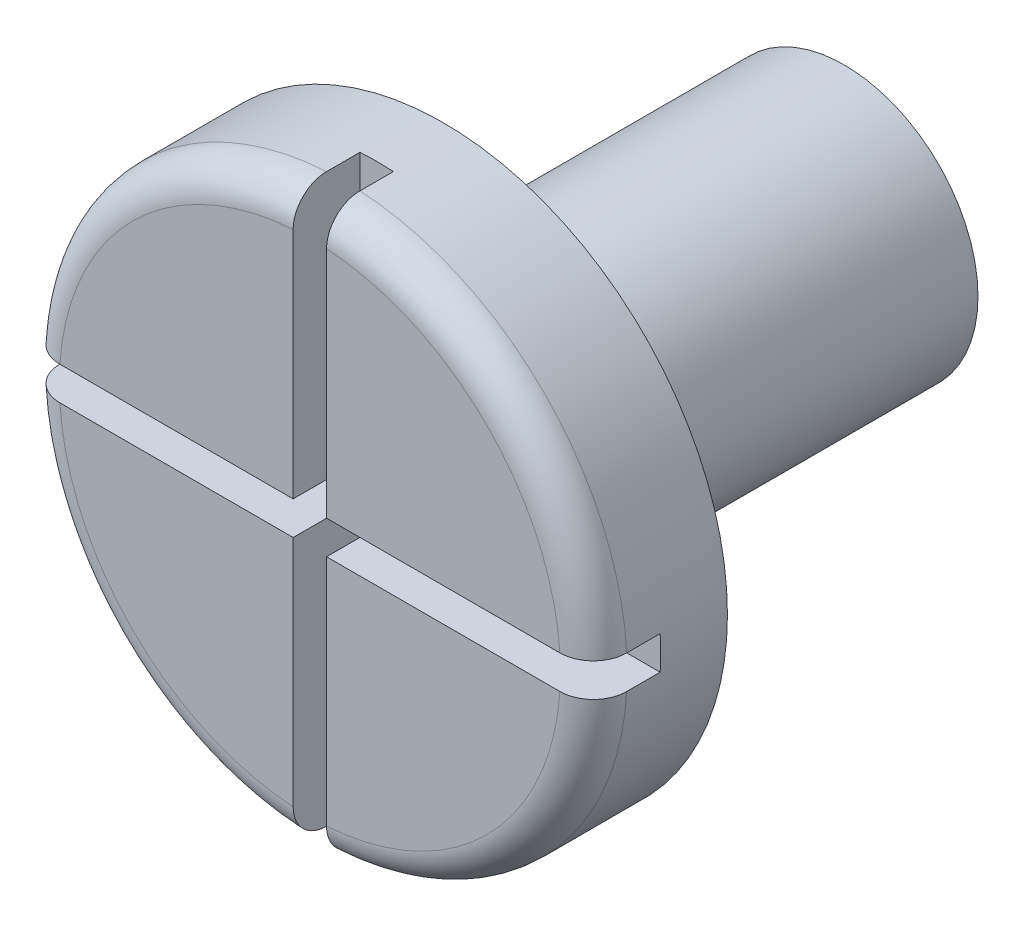
SolidWorks part; units mm, degrees
material "6061 Alloy"
ref_plane "Front Plane" through (0, 0, 0) normal (0, 0, 1) x (1, 0, 0)
ref_plane "Top Plane" through (0, 0, 0) normal (0, 1, 0) x (1, 0, 0)
ref_plane "Right Plane" through (0, 0, 0) normal (1, 0, 0) x (0, 0, -1)
sketch "Sketch1" plane through (0, 0, 0) normal (0, 0, 1) x (1, 0, 0)
  circle A0 centre (0, 0) radius 4.25
  dimension "D1" = 8.5
extrude "Boss-Extrude1" add sketch "Sketch1" against normal blind 2
sketch "Sketch2" plane through (0, 0, -2) normal (0, 0, -1) x (-1, 0, 0)
  circle A0 centre (0, 0) radius 2
  dimension "D1" = 4
extrude "Boss-Extrude2" add sketch "Sketch2" along normal blind 6
sketch "Sketch3" plane through (0, 0, 0) normal (0, 0, 1) x (1, 0, 0)
  line L0 (0, 4.25) -> (0, 0.25) construction
  line L2 (-4.25, -0.25) -> (-0.25, -0.25)
  line L3 (-0.25, 4.25) -> (-0.25, 0.25)
  line L4 (-4.25, 0.25) -> (-0.25, 0.25)
  line L5 (0.25, 4.25) -> (0.25, 0.25)
  line L6 (-0.25, 4.25) -> (0, 4.8094)
  line L7 (0, 4.8094) -> (0.25, 4.25)
  line L8 (4.25, 0.25) -> (4.8094, 0)
  line L9 (4.8094, 0) -> (4.25, -0.25)
  line L10 (-4.25, 0.25) -> (-4.9275, -0.0527)
  line L11 (-4.9275, -0.0527) -> (-4.25, -0.25)
  line L12 (-0.25, -4.25) -> (0.125, -4.818)
  line L13 (0.125, -4.818) -> (0.25, -4.25)
  line L14 (0.25, 0.25) -> (4.25, 0.25)
  line L16 (-0.25, -0.25) -> (-0.25, -4.25)
  line L17 (-0.25, 4.25) -> (-0.25, -4.25) construction
  line L20 (0, 4.25) -> (0, -4.25) construction
  line L21 (0.25, -0.25) -> (0.25, -4.25)
  line L22 (0.25, 4.25) -> (0.25, -4.25) construction
  line L23 (0.25, -0.25) -> (4.25, -0.25)
  circle A0 centre (0, 0) radius 4.25 construction
  point P6 (0, 0)
  dimension "D1" = 0.25
  dimension "D2" = 0.25
extrude "Cut-Extrude1" cut sketch "Sketch3" against normal blind 1
fillet "Fillet1" radius 0.5 4 edges at (-3.0052, -3.0052, 0) (3.0052, -3.0052, 0) (3.0052, 3.0052, 0) (-3.0052, 3.0052, 0)
